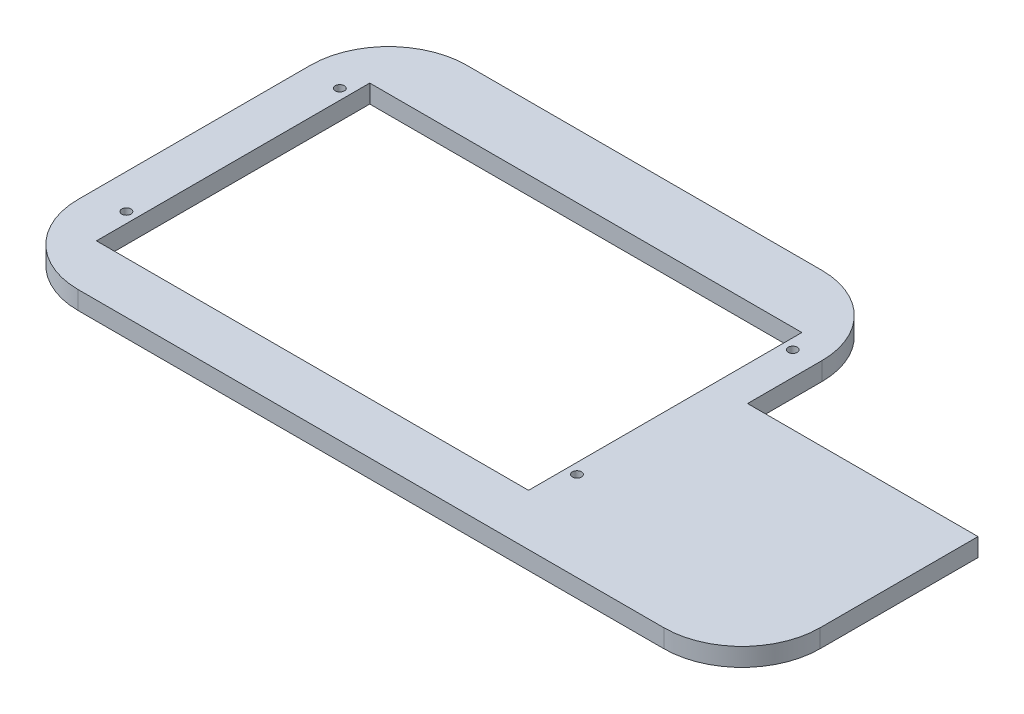
SolidWorks part; units mm, degrees
ref_plane "Front Plane" through (0, 0, 0) normal (0, 0, 1) x (1, 0, 0)
ref_plane "Top Plane" through (0, 0, 0) normal (0, 1, 0) x (1, 0, 0)
ref_plane "Right Plane" through (0, 0, 0) normal (1, 0, 0) x (0, 0, -1)
sketch "Sketch1" plane through (0, 0, 0) normal (0, 1, 0) x (1, 0, 0)
  line L0 (-19.1775, 42.2756) -> (117.3225, 42.2756)
  line L1 (-31.8659, 17.7318) -> (134.1341, 17.7318)
  line L2 (-31.8659, 17.7318) -> (-31.8659, -87.2682)
  line L3 (-31.8659, -87.2682) -> (134.1341, -87.2682)
  line L4 (134.1341, 17.7318) -> (134.1341, 10.2318)
  line L5 (-49.1775, 12.2756) -> (-49.1775, -76.9862)
  line L6 (-19.1775, -106.9862) -> (156.3225, -106.9862)
  line L7 (147.3225, 12.2756) -> (147.3225, -16.3244)
  line L9 (134.1341, -87.2682) -> (134.1341, -71.1682)
  line L11 (138.0341, -67.2682) -> (138.2341, -67.2682)
  line L12 (147.3225, -16.3244) -> (235.8493, -16.3244)
  line L13 (156.3225, -106.9862) -> (205.8493, -106.9862)
  line L14 (235.8493, -16.3244) -> (235.8493, -76.9862)
  line L15 (-35.8659, 57.978) -> (-35.8659, -149.533) construction
  line L16 (138.1341, 64.116) -> (138.1341, 8.4818) construction
  line L17 (-102.6051, 10.2318) -> (248.6764, 10.2318) construction
  line L18 (-106.6184, -71.7682) -> (142.1341, -71.7682) construction
  line L19 (142.1341, -71.1682) -> (142.1341, -71.7682)
  line L20 (134.1341, 10.2318) -> (134.1393, -34.2682)
  line L23 (134.1393, -34.2682) -> (134.1341, -71.1682)
  line L24 (138.1341, -70.9331) -> (138.1341, -149.533) construction
  line L25 (235.8493, -71.7682) -> (274.1727, -71.7682) construction
  arc A0 (117.3225, 42.2756) -> (147.3225, 12.2756) centre (117.3225, 12.2756) cw
  arc A1 (-19.1775, 42.2756) -> (-49.1775, 12.2756) centre (-19.1775, 12.2756) ccw
  arc A2 (205.8493, -106.9862) -> (235.8493, -76.9862) centre (205.8493, -76.9862) ccw
  arc A3 (-49.1775, -76.9862) -> (-19.1775, -106.9862) centre (-19.1775, -76.9862) ccw
  circle A4 centre (-35.8659, -71.7682) radius 1.75
  circle A5 centre (-35.8659, 10.2318) radius 1.75
  circle A6 centre (138.1341, -72.6831) radius 1.75
  circle A7 centre (138.1341, 10.2318) radius 1.75
  arc A9 (134.1341, -71.1682) -> (134.1341, -71.167) centre (138.0341, -71.1682) cw
  point P45 (142.1341, -67.2682)
  point P48 (134.1341, -67.2682)
  dimension "D3" = 30
  dimension "D8" = 20
  dimension "D1" = 166
  dimension "D2" = 105
  dimension "D4" = 4
  dimension "D5" = 4
  dimension "D6" = 7.5
  dimension "D7" = 15.5
  dimension "D9" = 8
extrude "Boss-Extrude1" add sketch "Sketch1" along normal blind 7
